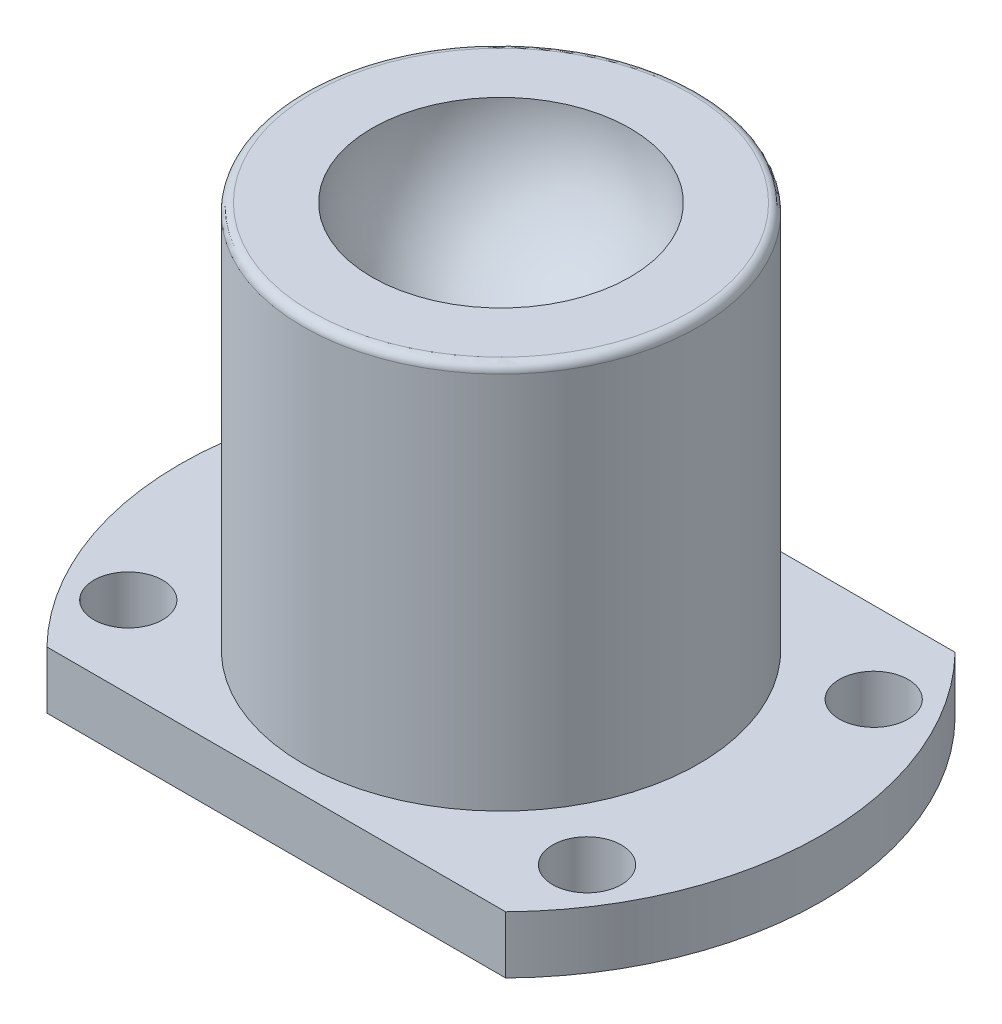
SolidWorks part; units mm, degrees
ref_plane "前视基准面" through (0, 0, 0) normal (0, 0, 1) x (1, 0, 0)
ref_plane "上视基准面" through (0, 0, 0) normal (0, 1, 0) x (1, 0, 0)
ref_plane "右视基准面" through (0, 0, 0) normal (1, 0, 0) x (0, 0, -1)
other "Configuration Table"
sketch "草图1" plane through (0, 0, 0) normal (0, 1, 0) x (1, 0, 0)
  circle A0 centre (0, 0) radius 11.2
  dimension "D1" = 22.4
extrude "凸台-拉伸1" add sketch "草图1" along normal blind 2
sketch "草图2" plane through (0, 2, 0) normal (0, 1, 0) x (1, 0, 0)
  line L1 (-8, -7.8384) -> (8, -7.8384)
  line L3 (-8, 7.8384) -> (8, 7.8384)
  circle A0 centre (0, 0) radius 11.2 construction
  arc A1 (8, -7.8384) -> (8, 7.8384) centre (0, 0) ccw
  circle A2 centre (0, 0) radius 11.2
  arc A3 (-8, 7.8384) -> (-8, -7.8384) centre (0, 0) ccw
  point P0 (0, 0)
  dimension "D2" = 16
  dimension "D3" = 16
  dimension "D1" = 0
extrude "切除-拉伸1" cut sketch "草图2" against normal blind 2 flip side to cut
sketch "草图3" plane through (0, 2, 0) normal (0, 1, 0) x (1, 0, 0)
  circle A0 centre (0, 0) radius 6.9
  dimension "D1" = 13.8
extrude "凸台-拉伸2" add sketch "草图3" along normal blind 13.5
sketch "草图4" plane through (0, 2, 0) normal (0, 1, 0) x (1, 0, 0)
  line L1 (-8, -5) -> (8, -5) construction
  line L2 (-8, -5) -> (-8, 5) construction
  line L3 (-8, 5) -> (8, 5) construction
  line L4 (8, -5) -> (8, 5) construction
  line L5 (-8, -5) -> (8, 5) construction
  line L6 (-8, 5) -> (8, -5) construction
  circle A0 centre (-8, 5) radius 1.2
  circle A1 centre (-8, -5) radius 1.2
  circle A2 centre (8, -5) radius 1.2
  circle A3 centre (8, 5) radius 1.2
  point P0 (0, 0)
  dimension "D3" = 2.4
  dimension "D4" = 2.4
  dimension "D5" = 2.4
  dimension "D6" = 2.4
  dimension "D1" = 16
  dimension "D2" = 10
extrude "切除-拉伸2" cut sketch "草图4" against normal blind 13.5
fillet "圆角1" radius 0.3 1 edges at (0, 15.5, 6.9)
sketch "草图5" plane through (0, 15.5, 0) normal (0, 1, 0) x (1, 0, 0)
  line L0 (0, -4.5) -> (0, 4.5) construction
  line L1 (0, 4.5) -> (0, -4.5)
  arc A0 (0, -4.5) -> (0, 4.5) centre (0, 0) ccw
  point P6 (0, 0)
  dimension "D1" = 9
revolve "切除-旋转1" cut sketch "草图5" angle 360 about L0
